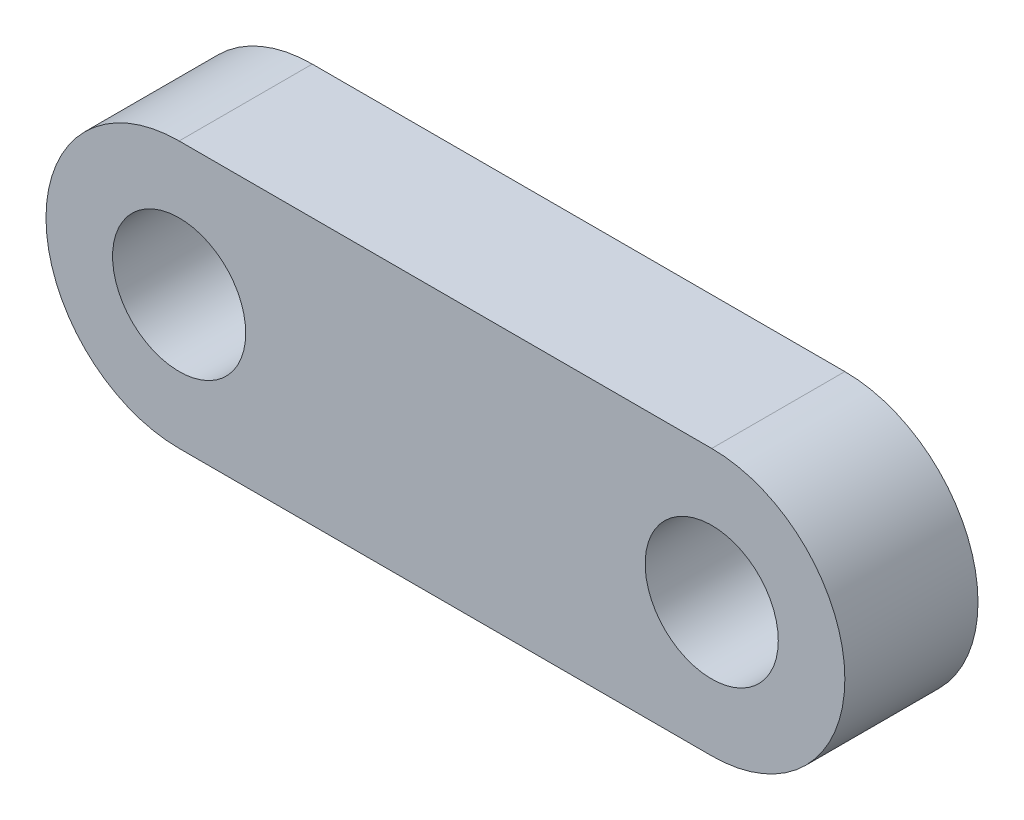
SolidWorks part; units mm, degrees
ref_plane "Front Plane" through (0, 0, 0) normal (0, 0, 1) x (1, 0, 0)
ref_plane "Top Plane" through (0, 0, 0) normal (0, 1, 0) x (1, 0, 0)
ref_plane "Right Plane" through (0, 0, 0) normal (1, 0, 0) x (0, 0, -1)
sketch "Sketch1" plane through (0, 0, 0) normal (0, 0, 1) x (1, 0, 0)
  line L0 (0, 0) -> (10, 0) construction
  line L1 (0, 2.5) -> (10, 2.5)
  line L2 (0, -2.5) -> (10, -2.5)
  arc A0 (0, 2.5) -> (0, -2.5) centre (0, 0) ccw
  arc A1 (10, -2.5) -> (10, 2.5) centre (10, 0) ccw
  circle A2 centre (0, 0) radius 1.25
  circle A3 centre (10, 0) radius 1.25
  point P3 (5, 0)
  dimension "D1" = 2.5
  dimension "D2" = 2.5
  dimension "D3" = 10
extrude "Boss-Extrude1" add sketch "Sketch1" along normal blind 2.5
